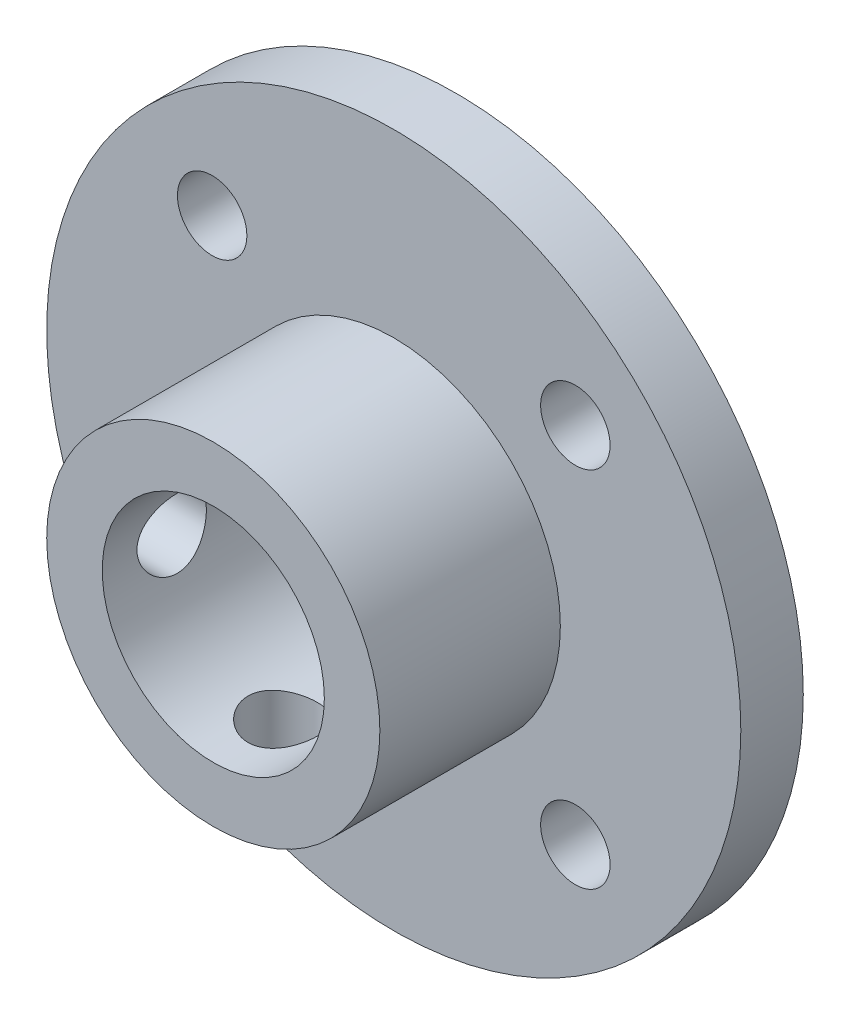
SolidWorks part; units mm, degrees
ref_plane "前视基准面" through (0, 0, 0) normal (0, 0, 1) x (1, 0, 0)
ref_plane "上视基准面" through (0, 0, 0) normal (0, 1, 0) x (1, 0, 0)
ref_plane "右视基准面" through (0, 0, 0) normal (1, 0, 0) x (0, 0, -1)
sketch "草图1" plane through (0, 0, 0) normal (0, 0, 1) x (1, 0, 0)
  line L0 (0, 18.5) -> (0, 0) construction
  line L1 (0, 0) -> (22.8966, 22.8966) construction
  circle A0 centre (0, 0) radius 25
  circle A6 centre (0, 0) radius 8
  circle A18 centre (13.0815, 13.0815) radius 2.5
  circle A19 centre (13.0815, -13.0815) radius 2.5
  circle A20 centre (-13.0815, -13.0815) radius 2.5
  circle A21 centre (-13.0815, 13.0815) radius 2.5
  dimension "D2" = 50
  dimension "D3" = 16
  dimension "D5" = 5
  dimension "D4" = 45
  dimension "D6" = 4
extrude "凸台-拉伸1" add sketch "草图1" along normal blind 4.5
sketch "草图2" plane through (0, 0, 4.5) normal (0, 0, 1) x (1, 0, 0)
  circle A0 centre (0, 0) radius 8
  circle A1 centre (0, 0) radius 12
extrude "凸台-拉伸2" add sketch "草图2" along normal blind 13
sketch "草图3" plane through (0, 0, 0) normal (0, 1, 0) x (1, 0, 0)
  circle A0 centre (0, -12.5) radius 2.5
  dimension "D1" = 5
  dimension "D2" = 12.5
extrude "切除-拉伸1" cut sketch "草图3" against normal blind 26
sketch "草图5" plane through (0, 0, 0) normal (1, 0, 0) x (0, 0, -1)
  line L1 (0, -25) -> (0, 25) construction
  circle A0 centre (-12.5, 0) radius 2.5
  dimension "D1" = 12.5
  dimension "D2" = 5
extrude "切除-拉伸4" cut sketch "草图5" against normal blind 26
equation "\"4.5.00mm\"=6"
